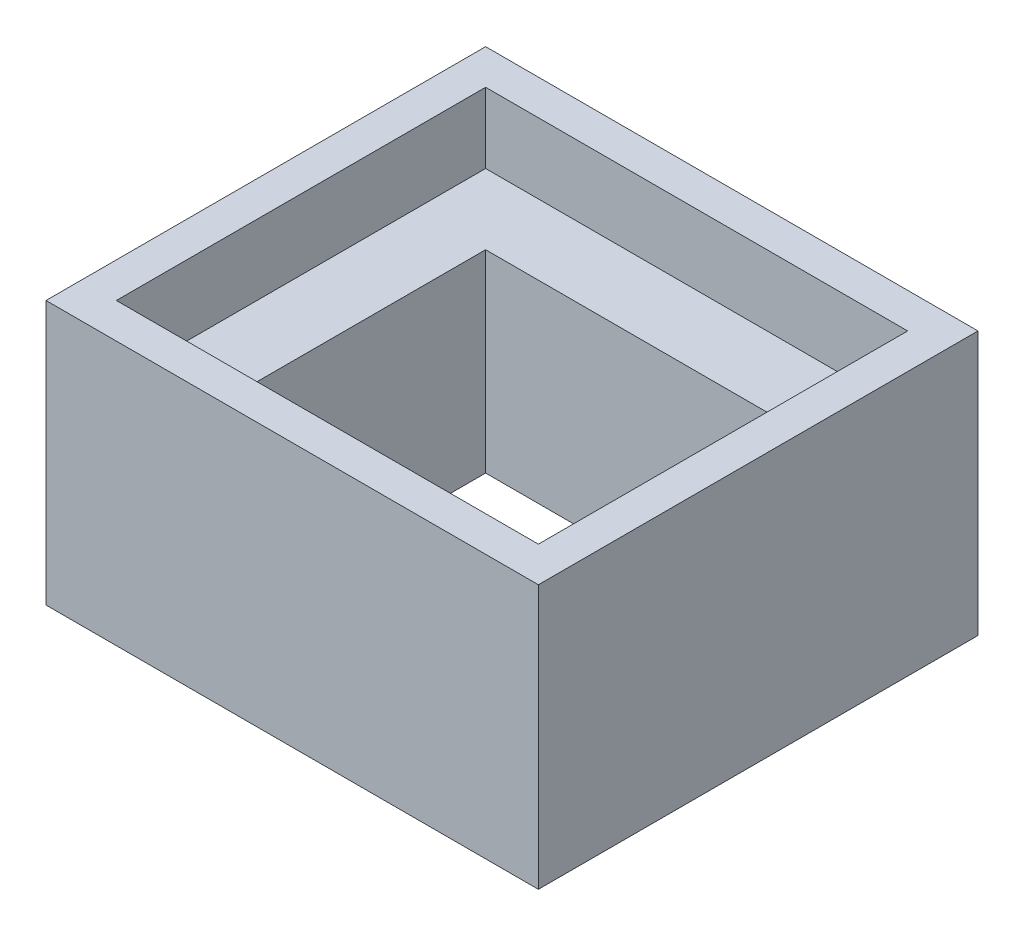
SolidWorks part; units mm, degrees
ref_plane "Front Plane" through (0, 0, 0) normal (0, 0, 1) x (1, 0, 0)
ref_plane "Top Plane" through (0, 0, 0) normal (0, 1, 0) x (1, 0, 0)
ref_plane "Right Plane" through (0, 0, 0) normal (1, 0, 0) x (0, 0, -1)
sketch "Sketch1" plane through (0, 0, 0) normal (0, 1, 0) x (1, 0, 0)
  line L1 (-28, -25) -> (28, -25)
  line L2 (-28, -25) -> (-28, 25)
  line L3 (-28, 25) -> (28, 25)
  line L4 (28, -25) -> (28, 25)
  line L5 (-28, -25) -> (28, 25) construction
  line L6 (-28, 25) -> (28, -25) construction
  point P0 (0, 0)
  dimension "D1" = 50
  dimension "D2" = 56
extrude "Boss-Extrude1" add sketch "Sketch1" along normal blind 30
sketch "Sketch3" plane through (0, 30, 0) normal (0, 1, 0) x (1, 0, 0)
  line L0 (28, 25) -> (-28, 25) construction
  line L1 (-24, -21) -> (24, -21)
  line L2 (-24, -21) -> (-24, 21)
  line L3 (-24, 21) -> (24, 21)
  line L4 (24, -21) -> (24, 21)
  line L5 (-24, -21) -> (24, 21) construction
  line L6 (-24, 21) -> (24, -21) construction
  line L7 (28, -25) -> (28, 25) construction
  point P0 (0, 0)
  dimension "D1" = 4
  dimension "D2" = 4
extrude "Cut-Extrude1" cut sketch "Sketch3" against normal blind 8
sketch "Sketch5" plane through (0, 22, 0) normal (0, 1, 0) x (1, 0, 0)
  line L0 (-24, 21) -> (-24, -21) construction
  line L1 (-16, -13) -> (16, -13)
  line L2 (-16, -13) -> (-16, 13)
  line L3 (-16, 13) -> (16, 13)
  line L4 (16, -13) -> (16, 13)
  line L5 (-16, -13) -> (16, 13) construction
  line L6 (-16, 13) -> (16, -13) construction
  line L7 (24, 21) -> (-24, 21) construction
  point P0 (0, 0)
  dimension "D1" = 8
  dimension "D2" = 8
extrude "Cut-Extrude2" cut sketch "Sketch5" against normal through all both and the other way through all
